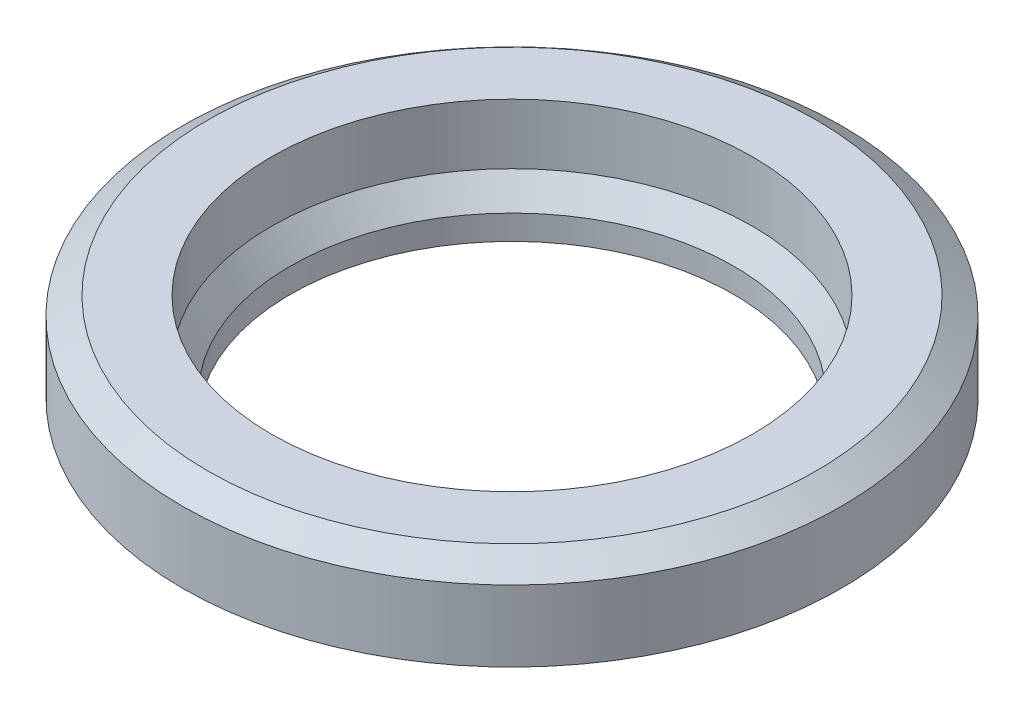
SolidWorks part; units mm, degrees
ref_plane "Alzado" through (0, 0, 0) normal (0, 0, 1) x (1, 0, 0)
ref_plane "Planta" through (0, 0, 0) normal (0, 1, 0) x (1, 0, 0)
ref_plane "Vista lateral" through (0, 0, 0) normal (1, 0, 0) x (0, 0, -1)
sketch "Croquis1" plane through (0, 0, 0) normal (0, 0, 1) x (1, 0, 0)
  line L11 (0, 26.0987) -> (0, -21.2147) construction
  line L12 (-8.0309, 0.5573) -> (-8.0309, 1.4454)
  line L13 (-8.0309, 0.5573) -> (-8.7087, 1.322)
  line L14 (-8.7087, 1.322) -> (-11.9373, 1.322)
  line L15 (-11.9373, 1.322) -> (-11.9373, 3.8956)
  line L16 (-11.9373, 3.8956) -> (-11.0156, 4.5393)
  line L20 (-8.7997, 4.5393) -> (8.8003, 4.5393) construction
  line L23 (-8.0309, 1.4454) -> (-8.7087, 2.3587)
  line L24 (-8.7087, 2.3587) -> (-8.7087, 4.5393)
  line L25 (-8.7087, 4.5393) -> (-11.0156, 4.5393)
  point P7 (-11.5088, 4.5393)
  point P10 (-10.6136, 4.5393)
  point P11 (-11.0156, 4.5393)
  point P12 (-8.5797, 1.6428)
  point P13 (-8.4477, 1.4434)
  point P15 (-8.7703, 1.6188)
  point P16 (-8.0073, 0.7964)
  point P17 (-8.7087, 2.3587)
  point P18 (-8.0217, 1.433)
  point P19 (-11.6554, 4.0925)
  point P20 (-8.0309, 0.5573)
  point P21 (0, 0)
  point P22 (-8.7087, 1.322)
revolve "Revolución1" add sketch "Croquis1" angle 360 about L11
fillet "Redondeo1" radius 1 1 edges at (0, 1.322, 8.7087)
